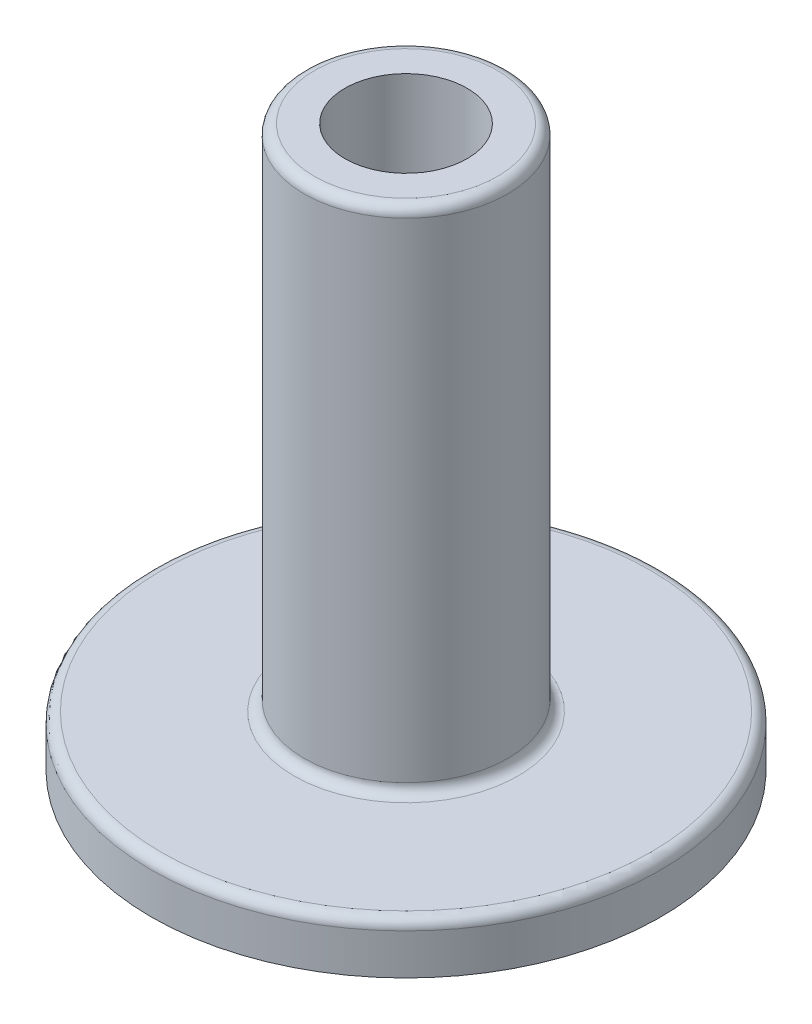
SolidWorks part; units mm, degrees
ref_plane "Front Plane" through (0, 0, 0) normal (0, 0, 1) x (1, 0, 0)
ref_plane "Top Plane" through (0, 0, 0) normal (0, 1, 0) x (1, 0, 0)
ref_plane "Right Plane" through (0, 0, 0) normal (1, 0, 0) x (0, 0, -1)
sketch "Sketch1" plane through (0, 0, 0) normal (0, 1, 0) x (1, 0, 0)
  circle A0 centre (0, 0) radius 25
  dimension "D1" = 50
extrude "Boss-Extrude1" add sketch "Sketch1" along normal blind 5
sketch "Sketch2" plane through (0, 5, 0) normal (0, 1, 0) x (1, 0, 0)
  circle A0 centre (0, 0) radius 10
  circle A1 centre (0, 0) radius 6
  dimension "D1" = 12
  dimension "D2" = 20
extrude "Boss-Extrude2" add sketch "Sketch2" along normal blind 50
fillet "Fillet1" radius 1 3 edges at (0, 5, 25) (0, 5, 10) (0, 55, 10)
